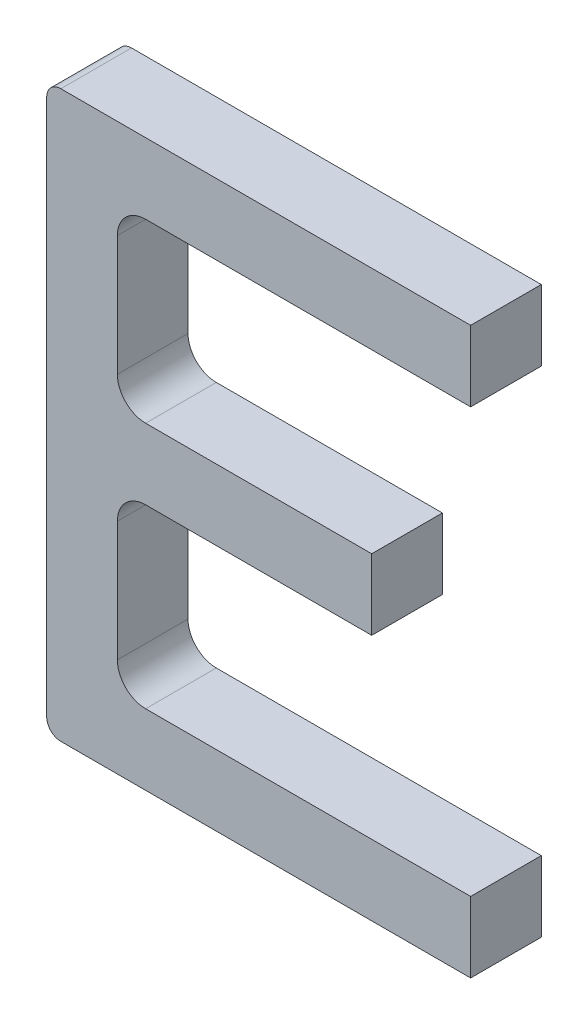
SolidWorks part; units mm, degrees
ref_plane "Front Plane" through (0, 0, 0) normal (0, 0, 1) x (1, 0, 0)
ref_plane "Top Plane" through (0, 0, 0) normal (0, 1, 0) x (1, 0, 0)
ref_plane "Right Plane" through (0, 0, 0) normal (1, 0, 0) x (0, 0, -1)
sketch "Sketch1" plane through (0, 0, 0) normal (0, 0, 1) x (1, 0, 0)
  line L1 (0, 0) -> (6.35, 0)
  line L2 (0, 0) -> (0, 50.8)
  line L3 (0, 50.8) -> (6.35, 50.8)
  line L4 (6.35, 0) -> (6.35, 50.8)
  line L5 (6.35, 50.8) -> (38.1, 50.8)
  line L6 (6.35, 50.8) -> (6.35, 44.45)
  line L7 (6.35, 44.45) -> (38.1, 44.45)
  line L8 (38.1, 50.8) -> (38.1, 44.45)
  line L9 (6.35, 28.575) -> (29.21, 28.575)
  line L10 (6.35, 28.575) -> (6.35, 22.225)
  line L11 (6.35, 22.225) -> (29.21, 22.225)
  line L12 (29.21, 28.575) -> (29.21, 22.225)
  line L13 (6.35, 0) -> (38.1, 0)
  line L14 (6.35, 0) -> (6.35, 6.35)
  line L15 (6.35, 6.35) -> (38.1, 6.35)
  line L16 (38.1, 0) -> (38.1, 6.35)
  point P15 (29.21, 25.4)
  point P16 (6.35, 25.4)
  dimension "D1" = 6.35
  dimension "D2" = 6.35
  dimension "D3" = 6.35
  dimension "D4" = 6.35
  dimension "D5" = 31.75
  dimension "D6" = 50.8
  dimension "D7" = 31.75
  dimension "D8" = 22.86
  dimension "D9" = 0
extrude "Boss-Extrude1" add sketch "Sketch1" along normal blind 6.35 contours L8 L5 L4 L7 | L1 L4 L3 L2 | L12 L9 L4 L11 | L13 L16 L15 L4
fillet "Fillet1" radius 2.54 4 edges at (6.35, 28.575, 3.175) (6.35, 22.225, 3.175) (6.35, 6.35, 3.175) (6.35, 44.45, 3.175)
fillet "Fillet2" radius 1.27 2 edges at (0, 0, 3.175) (0, 50.8, 3.175)
